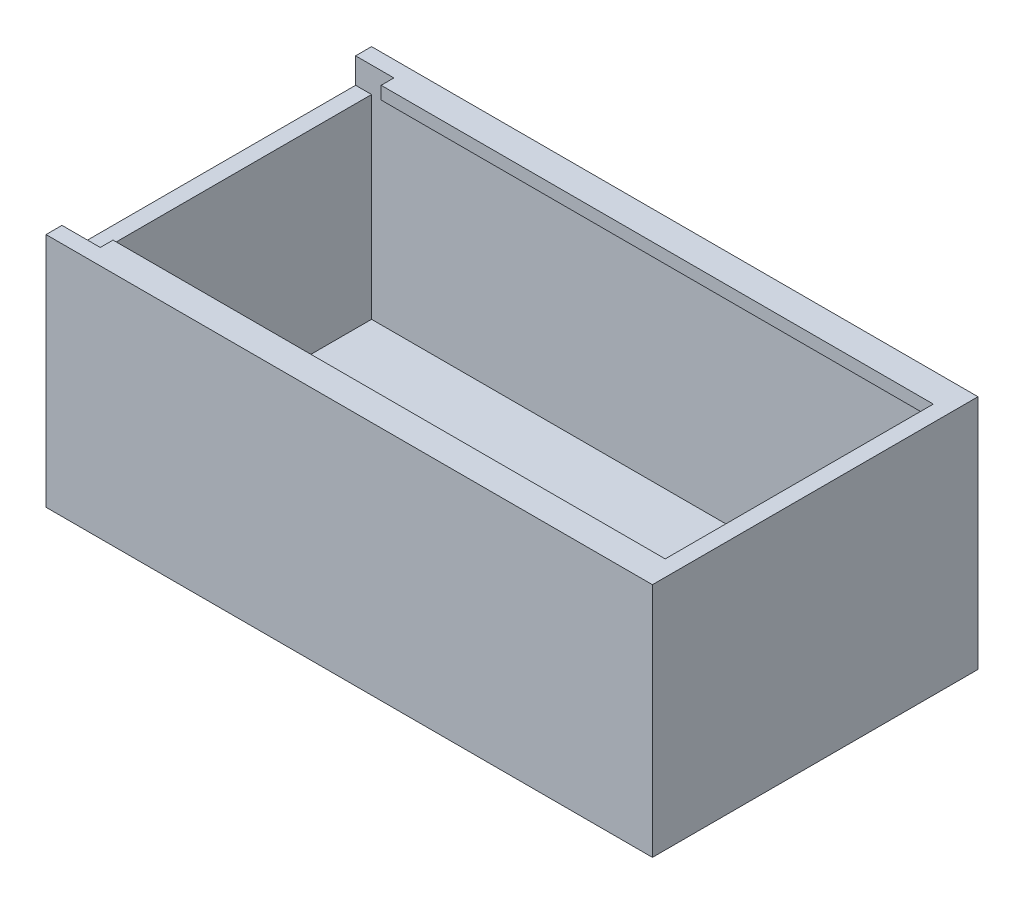
SolidWorks part; units mm, degrees
ref_plane "Plano frontal" through (0, 0, 0) normal (0, 0, 1) x (1, 0, 0)
ref_plane "Plano superior" through (0, 0, 0) normal (0, 1, 0) x (1, 0, 0)
ref_plane "Plano direito" through (0, 0, 0) normal (1, 0, 0) x (0, 0, -1)
sketch "Esboço1" plane through (0, 0, 0) normal (0, 1, 0) x (1, 0, 0)
  line L0 (0, 0) -> (95, 0)
  line L1 (95, 0) -> (95, -51)
  line L2 (95, -51) -> (0, -51)
  line L3 (0, -51) -> (0, 0)
  dimension "D1" = 95
  dimension "D2" = 51
extrude "Ressalto-extrusão1" add sketch "Esboço1" along normal blind 2.5
sketch "Esboço2" plane through (0, 0, 0) normal (0, 1, 0) x (1, 0, 0)
  line L1 (0, 0) -> (95, 0)
  line L2 (0, 0) -> (0, -51)
  line L3 (0, -51) -> (95, -51)
  line L4 (95, 0) -> (95, -51)
  line L5 (2.5, -2.5) -> (92.5, -2.5)
  line L6 (2.5, -2.5) -> (2.5, -48.5)
  line L7 (2.5, -48.5) -> (92.5, -48.5)
  line L8 (92.5, -2.5) -> (92.5, -48.5)
  dimension "D1" = 2.5
  dimension "D2" = 2.5
  dimension "D3" = 2.5
  dimension "D4" = 2.5
extrude "Ressalto-extrusão3" add sketch "Esboço2" along normal blind 37
sketch "Esboço3" plane through (0, 0, 0) normal (-1, 0, 0) x (0, 0, 1)
  line L0 (0, 37) -> (51, 37) construction
  line L1 (2.5, 37) -> (48.5, 37)
  line L2 (2.5, 37) -> (2.5, 33)
  line L3 (2.5, 33) -> (48.5, 33)
  line L4 (48.5, 37) -> (48.5, 33)
  line L5 (0, 37) -> (0, 0) construction
  line L6 (51, 37) -> (51, 0) construction
  dimension "D1" = 2.5
  dimension "D2" = 2.5
  dimension "D3" = 4
extrude "Corte-extrusão3" cut sketch "Esboço3" against normal blind 2.5
sketch "Esboço4" plane through (0, 0, 0) normal (-1, 0, 0) x (0, 0, 1)
  line L1 (2.5, 37) -> (4.5, 37)
  line L2 (2.5, 37) -> (2.5, 35)
  line L3 (2.5, 35) -> (4.5, 35)
  line L4 (4.5, 37) -> (4.5, 35)
  line L5 (48.5, 37) -> (46.5, 37)
  line L6 (48.5, 37) -> (48.5, 35)
  line L7 (48.5, 35) -> (46.5, 35)
  line L8 (46.5, 37) -> (46.5, 35)
  dimension "D1" = 2
  dimension "D2" = 2
  dimension "D3" = 2
  dimension "D4" = 2
extrude "Ressalto-extrusão7" add sketch "Esboço4" against normal blind 86.5 from offset 6
